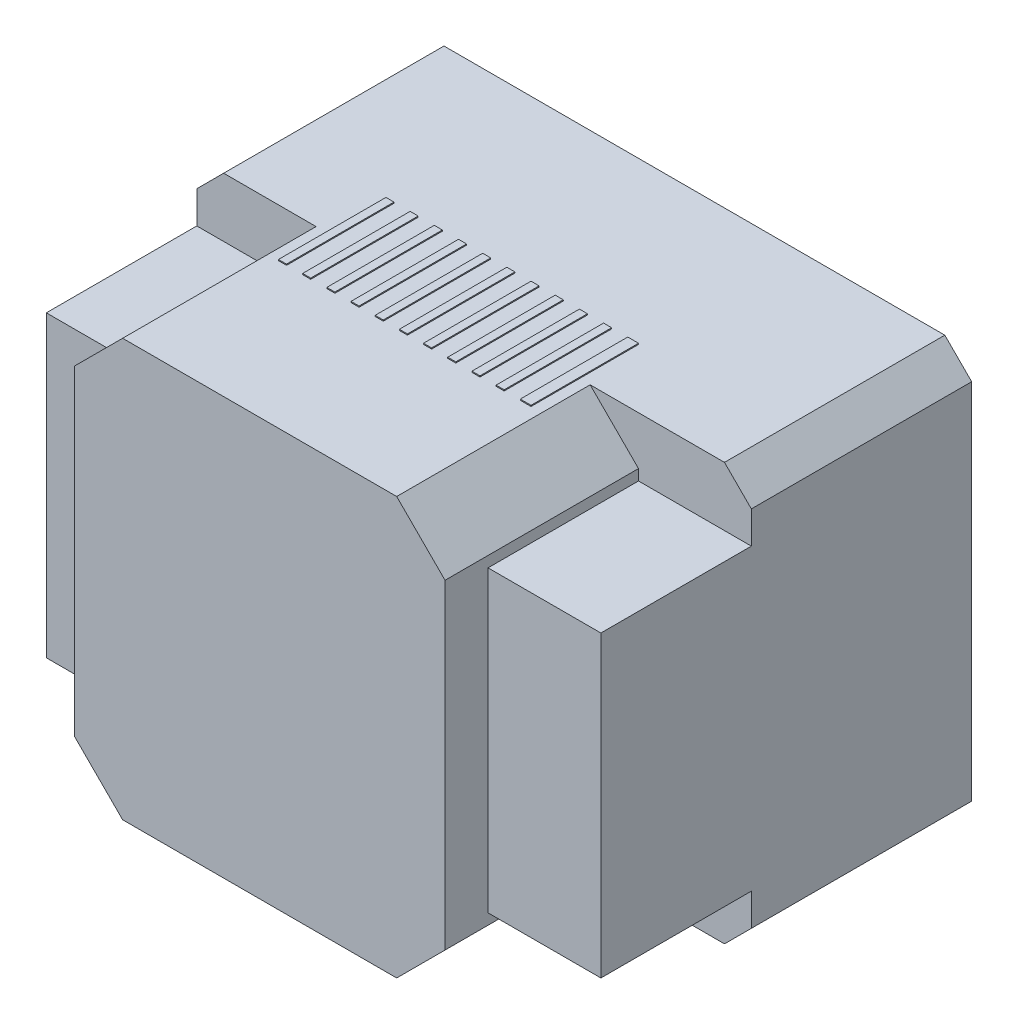
SolidWorks part; units mm, degrees
ref_plane "Front Plane" through (0, 0, 0) normal (0, 0, 1) x (1, 0, 0)
ref_plane "Top Plane" through (0, 0, 0) normal (0, 1, 0) x (1, 0, 0)
ref_plane "Right Plane" through (0, 0, 0) normal (1, 0, 0) x (0, 0, -1)
sketch "Sketch1" plane through (0, 0, 0) normal (0, 0, 1) x (1, 0, 0)
  line L1 (-25.8, 19.4) -> (25.8, 19.4)
  line L2 (-25.8, 19.4) -> (-25.8, -19.4)
  line L3 (-25.8, -19.4) -> (25.8, -19.4)
  line L4 (25.8, 19.4) -> (25.8, -19.4)
  line L5 (-25.8, 19.4) -> (25.8, -19.4) construction
  line L6 (-25.8, -19.4) -> (25.8, 19.4) construction
  point P0 (0, 0)
  dimension "D1" = 38.8
  dimension "D2" = 51.6
extrude "Boss-Extrude1" add sketch "Sketch1" along normal blind 20.5
sketch "Sketch2" plane through (0, 0, 20.5) normal (0, 0, 1) x (1, 0, 0)
  line L0 (25.8, -19.4) -> (25.8, 19.4) construction
  line L1 (25.8, 13.9) -> (-25.8, 13.9)
  line L2 (25.8, 13.9) -> (25.8, -13.9)
  line L3 (25.8, -13.9) -> (-25.8, -13.9)
  line L4 (-25.8, 13.9) -> (-25.8, -13.9)
  line L5 (-25.8, 19.4) -> (-25.8, -19.4) construction
  line L6 (25.8, 19.4) -> (-25.8, 19.4) construction
  line L7 (-25.8, -19.4) -> (25.8, -19.4) construction
  point P6 (-25.8, 0)
  point P9 (-25.8, 0)
  dimension "D1" = 5.5
  dimension "D2" = 5.5
extrude "Boss-Extrude2" add sketch "Sketch2" along normal blind 14
sketch "Sketch3" plane through (0, 0, 20.5) normal (0, 0, 1) x (1, 0, 0)
  line L0 (25.8, 19.4) -> (-25.8, 19.4) construction
  line L1 (15.3, 19.4) -> (-19.2, 19.4)
  line L2 (15.3, 19.4) -> (15.3, -19.4)
  line L3 (15.3, -19.4) -> (-19.2, -19.4)
  line L4 (-19.2, 19.4) -> (-19.2, -19.4)
  line L5 (-25.8, -19.4) -> (25.8, -19.4) construction
  line L7 (25.8, 13.9) -> (25.8, 19.4) construction
  dimension "D1" = 34.5
  dimension "D2" = 10.5
extrude "Boss-Extrude3" add sketch "Sketch3" along normal blind 18
sketch "Sketch4" plane through (0, -19.4, 0) normal (0, -1, 0) x (1, 0, 0)
  line L0 (-25.8, 0) -> (25.8, 0) construction
  line L1 (-13.7, 25) -> (9.8, 25)
  line L2 (-13.7, 25) -> (-13.7, 15)
  line L3 (-13.7, 15) -> (9.8, 15)
  line L4 (9.8, 25) -> (9.8, 15)
  line L5 (-13.7, 25) -> (9.8, 15) construction
  line L6 (-13.7, 15) -> (9.8, 25) construction
  line L7 (-19.2, 38.5) -> (15.3, 38.5) construction
  line L8 (-12.95, 25) -> (-12.95, 15)
  line L9 (-11.45, 25) -> (-11.45, 15)
  line L10 (-10.7, 25) -> (-10.7, 15)
  line L11 (-9.2, 25) -> (-9.2, 15)
  line L12 (-8.45, 25) -> (-8.45, 15)
  line L13 (-6.95, 25) -> (-6.95, 15)
  line L14 (-6.2, 25) -> (-6.2, 15)
  line L15 (-4.7, 25) -> (-4.7, 15)
  line L16 (-3.95, 25) -> (-3.95, 15)
  line L17 (-2.45, 25) -> (-2.45, 15)
  line L18 (-1.7, 25) -> (-1.7, 15)
  line L19 (-0.2, 25) -> (-0.2, 15)
  line L20 (0.55, 25) -> (0.55, 15)
  line L21 (2.05, 25) -> (2.05, 15)
  line L22 (2.8, 25) -> (2.8, 15)
  line L23 (4.3, 25) -> (4.3, 15)
  line L24 (5.05, 25) -> (5.05, 15)
  line L25 (6.55, 25) -> (6.55, 15)
  line L26 (7.3, 25) -> (7.3, 15)
  line L27 (8.8, 25) -> (8.8, 15)
  point P0 (-1.95, 20)
  point P7 (-1.95, 25)
  point P10 (-1.95, 38.5)
  dimension "D1" = 15
  dimension "D2" = 23.5
  dimension "D3" = 10
  dimension "D4" = 0.75
  dimension "D5" = 1.5
  dimension "D6" = 10
extrude "Boss-Extrude4" add sketch "Sketch4" along normal blind 0.1 contours L8 L1 L2 L3 | L10 L1 L9 L3 | L12 L1 L11 L3 | L14 L1 L13 L3 | L16 L1 L15 L3 | L18 L1 L17 L3 | L20 L1 L19 L3 | L22 L1 L21 L3 | L24 L1 L23 L3 | L26 L1 L25 L3 | L1 L27 L3 L4
mirror "Mirror1" about plane through (0, 0, 0) normal (0, 1, 0) of "Boss-Extrude4"
chamfer "Chamfer1" distance 2.5 angle 45 4 edges at (25.8, 19.4, 10.25) (-25.8, 19.4, 10.25) (25.8, -19.4, 10.25) (-25.8, -19.4, 10.25)
chamfer "Chamfer2" distance 4.5 angle 45 4 edges at (15.3, -19.4, 29.5) (-19.2, -19.4, 29.5) (-19.2, 19.4, 29.5) (15.3, 19.4, 29.5)
